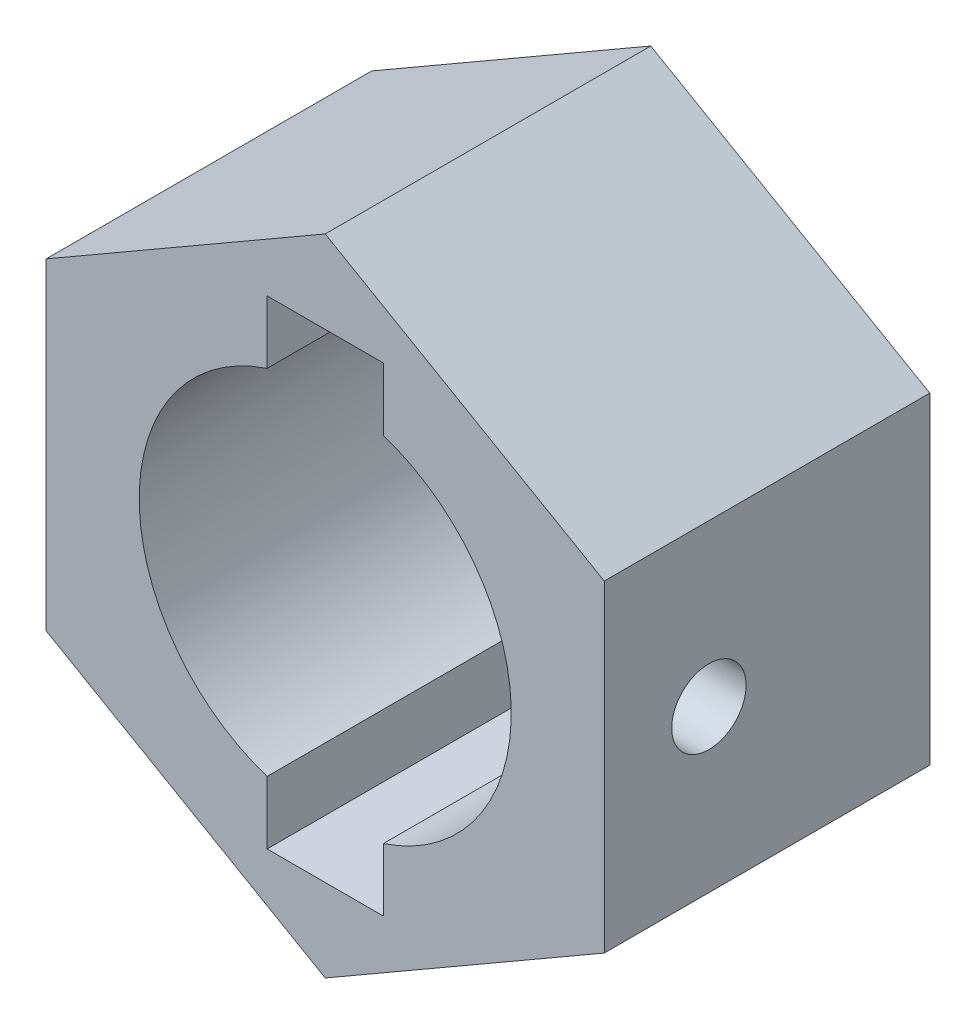
SolidWorks part; units mm, degrees
material "6061 Alloy"
ref_plane "Front Plane" through (0, 0, 0) normal (0, 0, 1) x (1, 0, 0)
ref_plane "Top Plane" through (0, 0, 0) normal (0, 1, 0) x (1, 0, 0)
ref_plane "Right Plane" through (0, 0, 0) normal (1, 0, 0) x (0, 0, -1)
sketch "Sketch1" plane through (0, 0, 0) normal (0, 0, 1) x (1, 0, 0)
  line L0 (-2.5, 7.5993) -> (-2.5, 10.3)
  line L1 (0, 13.8564) -> (-12, 6.9282)
  line L2 (-12, 6.9282) -> (-12, -6.9282)
  line L3 (-12, -6.9282) -> (0, -13.8564)
  line L4 (0, -13.8564) -> (12, -6.9282)
  line L5 (12, -6.9282) -> (12, 6.9282)
  line L6 (12, 6.9282) -> (0, 13.8564)
  line L7 (-2.5, 10.3) -> (2.5, 10.3)
  line L8 (2.5, 10.3) -> (2.5, 7.5993)
  line L9 (-2.5, -7.5993) -> (-2.5, -10.3)
  line L10 (-2.5, -10.3) -> (2.5, -10.3)
  line L11 (2.5, -10.3) -> (2.5, -7.5993)
  circle A0 centre (0, 0) radius 8
  circle A1 centre (0, 0) radius 12 construction
  dimension "D1" = 24
  dimension "D2" = 16
  dimension "D3" = 5
  dimension "D4" = 2.5
  dimension "D5" = 10.3
  dimension "D6" = 10.3
extrude "Boss-Extrude1" add sketch "Sketch1" along normal blind 14 contours L5 L6 L1 L2 L3 L4 A0 L0 L7 L8 L11 L10 L9
hole_wizard "M3 Clearance Hole1" positions "Sketch3" profile "Sketch4" hole size "M3" standard "ANSI Metric"
sketch "Sketch3" plane through (12, 0, 0) normal (1, 0, 0) x (0, 0, -1)
  line L0 (0, -6.9282) -> (0, 6.9282) construction
  line L1 (-14, 6.9282) -> (0, 6.9282) construction
  line L2 (-9.5, 6.9282) -> (-9.5, -6.9282) construction
  line L3 (-14, -6.9282) -> (0, -6.9282) construction
  point P0 (-9.5, 0)
  dimension "D1" = 9.5
sketch "Sketch4" plane through (12, 0, 9.5) normal (0, 1, 0) x (0, 0, -1)
  line L0 (0, 0) -> (0, 4)
  line L1 (0, 4) -> (1.6, 4)
  line L2 (1.6, 4) -> (1.6, 0)
  line L5 (1.6, 0) -> (0, 0)
  line L11 (0, -6.35) -> (0, 107.95) construction
  dimension "Thru Hole Dia." = 3.2
  dimension "Thru Hole Depth" = 4
hole_wizard "M2x0.4 Tapped Hole1" positions "Sketch7" profile "Sketch6" tap size "M2x0.4" standard "ANSI Metric"
sketch "Sketch7" plane through (-12, 0, 0) normal (-1, 0, 0) x (0, 0, 1)
  line L0 (0, 6.9282) -> (0, -6.9282) construction
  line L1 (2, -6.9282) -> (2, 6.9282) construction
  line L2 (14, -6.9282) -> (0, -6.9282) construction
  line L3 (14, 6.9282) -> (0, 6.9282) construction
  point P0 (2, 0)
  dimension "D1" = 2
sketch "Sketch6" plane through (-12, 0, 2) normal (0, 1, 0) x (0, 0, 1)
  line L0 (0, 0) -> (0, 4)
  line L1 (0, 4) -> (0.8, 4)
  line L2 (0.8, 4) -> (0.8, 0)
  line L5 (0.8, 0) -> (0, 0)
  line L11 (0, -6.35) -> (0, 107.95) construction
  dimension "Thru Tap Drill Dia." = 1.6
  dimension "Thru Tap Drill Depth" = 4
cosmetic thread "Hole Thread1"
